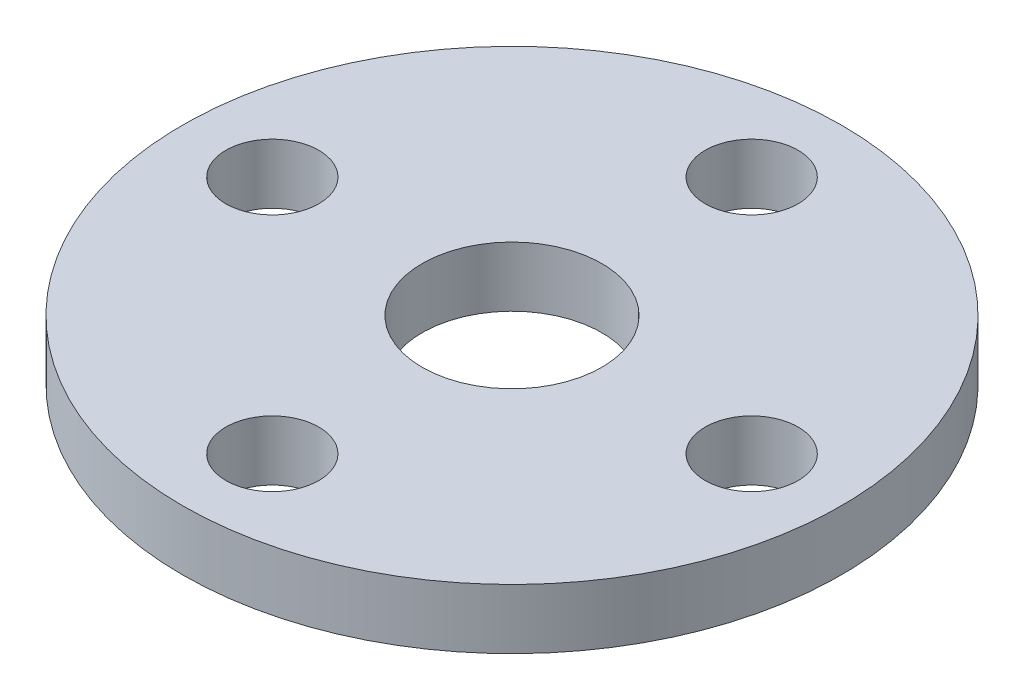
SolidWorks part; units mm, degrees
ref_plane "前基準面" through (0, 0, 0) normal (0, 0, 1) x (1, 0, 0)
ref_plane "上基準面" through (0, 0, 0) normal (0, 1, 0) x (1, 0, 0)
ref_plane "右基準面" through (0, 0, 0) normal (1, 0, 0) x (0, 0, -1)
sketch "草圖1" plane through (0, 0, 0) normal (0, 1, 0) x (1, 0, 0)
  line L0 (0, 0) -> (0, 8) construction
  line L1 (0, 0) -> (8, 0) construction
  line L2 (0, 0) -> (0, -8) construction
  line L3 (0, 0) -> (-8, 0) construction
  circle A0 centre (0, 0) radius 11
  circle A1 centre (0, 8) radius 1.55
  circle A2 centre (8, 0) radius 1.55
  circle A3 centre (0, -8) radius 1.55
  circle A4 centre (-8, 0) radius 1.55
  circle A5 centre (0, 0) radius 3
  point P14 (0, 0)
  dimension "D1" = 22
  dimension "D3" = 3.1
  dimension "D5" = 6
  dimension "D2" = 8
  dimension "D4" = 4
extrude "填料-伸長1" add sketch "草圖1" along normal blind 2
